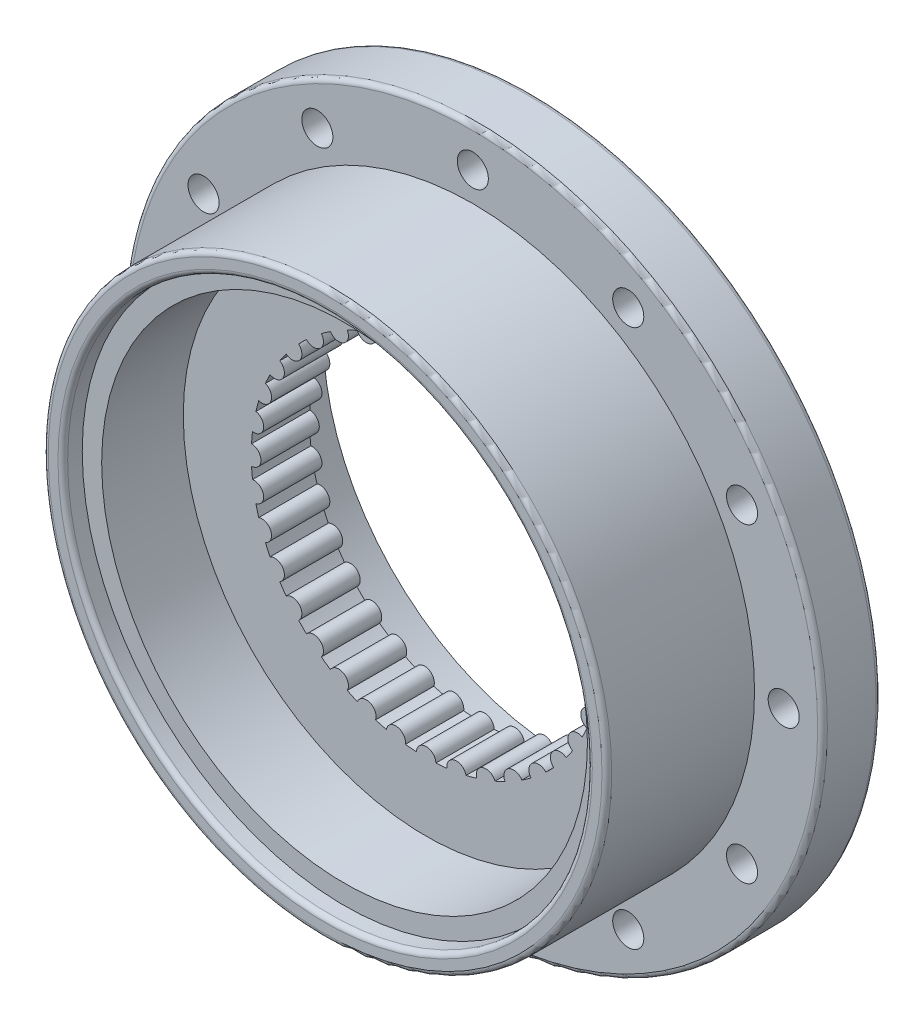
SolidWorks part; units mm, degrees
ref_plane "Plan de face" through (0, 0, 0) normal (0, 0, 1) x (1, 0, 0)
ref_plane "Plan de dessus" through (0, 0, 0) normal (0, 1, 0) x (1, 0, 0)
ref_plane "Plan de droite" through (0, 0, 0) normal (1, 0, 0) x (0, 0, -1)
sketch "Esquisse1" plane through (0, 0, 0) normal (1, 0, 0) x (0, 0, -1)
  line L0 (0, 125) -> (0, 145)
  line L2 (-48, 180) -> (-48, 145)
  line L3 (-48, 145) -> (-124, 145)
  line L4 (-124, 145) -> (-124, 135)
  line L5 (-124, 135) -> (-114, 135)
  line L6 (-114, 135) -> (-114, 125)
  line L7 (-114, 125) -> (-72, 125)
  line L8 (-72, 125) -> (-72, 90)
  line L9 (-72, 90) -> (-42, 90)
  line L10 (-42, 90) -> (-42, 125)
  line L11 (-42, 125) -> (0, 125)
  line L12 (0, 0) -> (-136.0654, 0) construction
  line L13 (0, 145) -> (-18, 145)
  line L14 (-18, 145) -> (-18, 180)
  line L15 (-18, 180) -> (-48, 180)
  dimension "D1" = 90
  dimension "D2" = 125
  dimension "D3" = 125
  dimension "D4" = 30
  dimension "D5" = 42
  dimension "D6" = 42
  dimension "D7" = 135
  dimension "D8" = 145
  dimension "D9" = 10
  dimension "D10" = 30
  dimension "D11" = 18
  dimension "D12" = 180
revolve "Révolution1" add sketch "Esquisse1" angle 360 about L12
sketch "Esquisse2" plane through (0, 0, 48) normal (0, 0, 1) x (1, 0, 0)
  line L0 (0, 0) -> (0, 160) construction
  circle A15 centre (0, 160) radius 8
  circle A17 centre (80, 138.5641) radius 8
  circle A18 centre (138.5641, 80) radius 8
  circle A19 centre (160, 0) radius 8
  circle A20 centre (138.5641, -80) radius 8
  circle A21 centre (80, -138.5641) radius 8
  circle A22 centre (0, -160) radius 8
  circle A23 centre (-80, -138.5641) radius 8
  circle A24 centre (-138.5641, -80) radius 8
  circle A25 centre (-160, 0) radius 8
  circle A26 centre (-138.5641, 80) radius 8
  circle A27 centre (-80, 138.5641) radius 8
  dimension "D1" = 16
  dimension "D3" = 12
  dimension "D4" = 160
extrude "Enlèv. mat.-Extru.1" cut sketch "Esquisse2" against normal through all both and the other way through all
sketch "Esquisse5" plane through (0, 0, 42) normal (0, 0, -1) x (-1, 0, 0)
  line L0 (0, 0) -> (0, 90) construction
  circle A0 centre (0, 90) radius 5
  circle A1 centre (0, 0) radius 90 construction
  circle A2 centre (15.6283, 88.6327) radius 5
  circle A3 centre (30.7818, 84.5723) radius 5
  circle A4 centre (45, 77.9423) radius 5
  circle A5 centre (57.8509, 68.944) radius 5
  circle A6 centre (68.944, 57.8509) radius 5
  circle A7 centre (77.9423, 45) radius 5
  circle A8 centre (84.5723, 30.7818) radius 5
  circle A9 centre (88.6327, 15.6283) radius 5
  circle A10 centre (90, 0) radius 5
  circle A11 centre (88.6327, -15.6283) radius 5
  circle A12 centre (84.5723, -30.7818) radius 5
  circle A13 centre (77.9423, -45) radius 5
  circle A14 centre (68.944, -57.8509) radius 5
  circle A15 centre (57.8509, -68.944) radius 5
  circle A16 centre (45, -77.9423) radius 5
  circle A17 centre (30.7818, -84.5723) radius 5
  circle A18 centre (15.6283, -88.6327) radius 5
  circle A19 centre (0, -90) radius 5
  circle A20 centre (-15.6283, -88.6327) radius 5
  circle A21 centre (-30.7818, -84.5723) radius 5
  circle A22 centre (-45, -77.9423) radius 5
  circle A23 centre (-57.8509, -68.944) radius 5
  circle A24 centre (-68.944, -57.8509) radius 5
  circle A25 centre (-77.9423, -45) radius 5
  circle A26 centre (-84.5723, -30.7818) radius 5
  circle A27 centre (-88.6327, -15.6283) radius 5
  circle A28 centre (-90, 0) radius 5
  circle A29 centre (-88.6327, 15.6283) radius 5
  circle A30 centre (-84.5723, 30.7818) radius 5
  circle A31 centre (-77.9423, 45) radius 5
  circle A32 centre (-68.944, 57.8509) radius 5
  circle A33 centre (-57.8509, 68.944) radius 5
  circle A34 centre (-45, 77.9423) radius 5
  circle A35 centre (-30.7818, 84.5723) radius 5
  circle A36 centre (-15.6283, 88.6327) radius 5
  dimension "D1" = 10
  dimension "D3" = 90
  dimension "D2" = 36
extrude "Boss.-Extru.1" add sketch "Esquisse5" against normal blind 30
fillet "Congé1" radius 2.5 5 edges at (-135, 0, 124) (-145, 0, 0) (-180, 0, 18) (-180, 0, 48) (-145, 0, 124)
